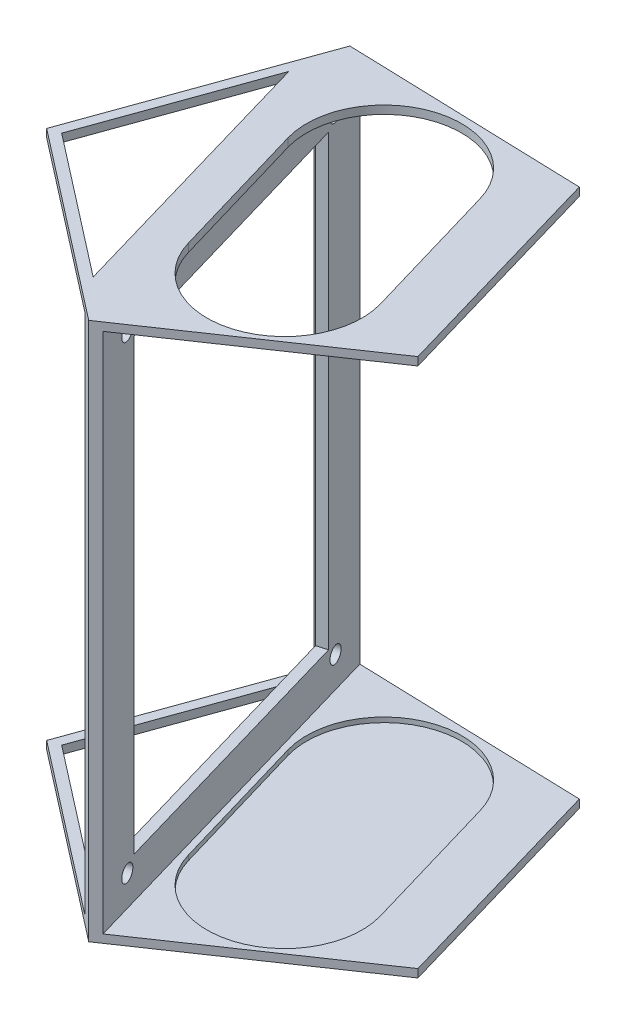
SolidWorks part; units mm, degrees
ref_plane "Front Plane" through (0, 0, 0) normal (0, 0, 1) x (1, 0, 0)
ref_plane "Top Plane" through (0, 0, 0) normal (0, 1, 0) x (1, 0, 0)
ref_plane "Right Plane" through (0, 0, 0) normal (1, 0, 0) x (0, 0, -1)
sketch "Sketch1" plane through (0, 0, 0) normal (0, 1, 0) x (1, 0, 0)
  line L1 (23.2611, -8.3705) -> (15.1489, 19.536)
  line L2 (15.1489, 19.536) -> (-13.8986, 20.4445)
  line L3 (-13.8986, 20.4445) -> (-23.7387, -6.9006)
  line L4 (-23.7387, -6.9006) -> (-0.7728, -24.7093)
  line L5 (-0.7728, -24.7093) -> (23.2611, -8.3705)
  circle A0 centre (0, 0) radius 20 construction
  point P1 (0, 0)
extrude "Boss-Extrude1" add sketch "Sketch1" along normal blind 1
sketch "Sketch2" plane through (0, 1, 0) normal (0, 1, 0) x (1, 0, 0)
  line L0 (-0.7728, -24.7093) -> (-13.8986, 20.4445) construction
  line L1 (-2.9239, -23.0412) -> (-14.8202, 17.8832)
  line L2 (-23.7387, -6.9006) -> (-0.7728, -24.7093) construction
  line L3 (-13.8986, 20.4445) -> (-23.7387, -6.9006) construction
  line L4 (0.2707, -23.9999) -> (-12.6374, 20.405)
  line L5 (-0.7728, -24.7093) -> (23.2611, -8.3705) construction
  line L6 (15.1489, 19.536) -> (-13.8986, 20.4445) construction
  line L7 (-14.8202, 17.8832) -> (-13.8986, 20.4445)
  line L13 (-0.7728, -24.7093) -> (23.2611, -8.3705)
  line L14 (23.2611, -8.3705) -> (15.1489, 19.536)
  line L15 (15.1489, 19.536) -> (-13.8986, 20.4445)
  line L16 (-13.8986, 20.4445) -> (-23.7387, -6.9006)
  line L17 (-23.7387, -6.9006) -> (-0.7728, -24.7093)
  line L18 (-0.7728, -24.7093) -> (0.2707, -23.9999)
  line L20 (-12.6374, 20.405) -> (-13.8986, 20.4445)
  line L21 (-13.8986, 20.4445) -> (-14.8202, 17.8832)
  line L22 (-2.9239, -23.0412) -> (-0.7728, -24.7093)
  line M10 (-0.7728, -24.7093) -> (23.2611, -8.3705)
  line M12 (15.1489, 19.536) -> (-13.8986, 20.4445)
  line M13 (-13.8986, 20.4445) -> (-23.7387, -6.9006)
  line M14 (-23.7387, -6.9006) -> (-0.7728, -24.7093)
  dimension "D1" = 1.2
  dimension "D2" = 1.6
  dimension "D3" = 0
extrude "Boss-Extrude2" add sketch "Sketch2" along normal blind 65 contours L0 L1 M14 M13 | L0 L4 M10 M12
sketch "Sketch3" plane through (0, 1, 0) normal (0, 1, 0) x (1, 0, 0)
  line L0 (10.2933, 12.2338) -> (15.3581, -5.0389)
  line L3 (-7.9391, 6.8877) -> (-2.8743, -10.3851)
  line L4 (-23.7201, -6.9646) -> (0.0025, -0.0086) construction
  line L5 (6.2419, -7.712) -> (1.1771, 9.5607) construction
  arc A0 (15.3581, -5.0389) -> (-2.8743, -10.3851) centre (6.2419, -7.712) cw
  arc A1 (10.2933, 12.2338) -> (-7.9391, 6.8877) centre (1.1771, 9.5607) ccw
  point P6 (-1.496, 18.6769)
  point P7 (8.915, -16.8282)
  dimension "D1" = 37
  dimension "D2" = 19
sketch "Sketch4" plane through (-8.8721, 0, 2.579) normal (-0.9603, 0, 0.2791) x (0.2791, 0, 0.9603)
  line L0 (-21.3092, 66) -> (21.3092, 1) construction
  line L1 (21.3092, 1) -> (-21.3092, 1) construction
  line L2 (21.3092, 66) -> (-21.3092, 1) construction
  line L3 (0, 63.5) -> (0, 3.5) construction
  line L4 (-20, 63.5) -> (20, 63.5)
  line L5 (-20, 63.5) -> (-20, 3.5)
  line L6 (-20, 3.5) -> (20, 3.5)
  line L7 (20, 63.5) -> (20, 3.5)
  line L8 (-20, 63.5) -> (20, 3.5) construction
  line L9 (-20, 3.5) -> (20, 63.5) construction
  line L10 (-20, 33.5) -> (20, 33.5) construction
  point P12 (0, 33.5)
  dimension "D1" = 40
  dimension "D2" = 60
extrude "Cut-Extrude1" cut sketch "Sketch4" against normal blind 1.5
sketch "Sketch5" plane through (-7.4317, 0, 2.1603) normal (-0.9603, 0, 0.2791) x (0.2791, 0, 0.9603)
  line L8 (17.5, 6) -> (17.5, 61)
  line L9 (17.5, 61) -> (-17.5, 61)
  line L10 (-17.5, 61) -> (-17.5, 6)
  line L11 (-17.5, 6) -> (17.5, 6)
  line L12 (17.5, 6) -> (17.5, 61)
  line L13 (17.5, 61) -> (-17.5, 61)
  line L14 (-17.5, 61) -> (-17.5, 6)
  line L15 (-17.5, 6) -> (17.5, 6)
  dimension "D1" = 2.5
extrude "Cut-Extrude2" cut sketch "Sketch5" against normal up to surface (1.3 mm away) up to face at (-6.1834, 33.5, 1.7974)
sketch "Sketch7" plane through (0, 66, 0) normal (0, 1, 0) x (1, 0, 0)
  line L5 (-0.7728, -24.7093) -> (23.2611, -8.3705)
  line L6 (-23.7387, -6.9006) -> (-0.7728, -24.7093)
  line L7 (-13.8986, 20.4445) -> (-23.7387, -6.9006)
  line L8 (15.1489, 19.536) -> (-13.8986, 20.4445)
  line L9 (23.2611, -8.3705) -> (15.1489, 19.536)
  line L10 (-0.7728, -24.7093) -> (23.2611, -8.3705)
  line L11 (-23.7387, -6.9006) -> (-0.7728, -24.7093)
  line L12 (-13.8986, 20.4445) -> (-23.7387, -6.9006)
  line L13 (15.1489, 19.536) -> (-13.8986, 20.4445)
  line L14 (23.2611, -8.3705) -> (15.1489, 19.536)
  dimension "D1" = 0
extrude "Boss-Extrude3" add sketch "Sketch7" against normal blind 1
sketch "Sketch6" plane through (0, 1, 0) normal (0, 1, 0) x (1, 0, 0)
  line L6 (-22.3144, -6.4866) -> (-5.1071, -19.8298)
  line L7 (-5.1071, -19.8298) -> (-14.9416, 14.0018)
  line L8 (-14.9416, 14.0018) -> (-22.3144, -6.4866)
  line L9 (-22.3144, -6.4866) -> (-5.1071, -19.8298)
  line L10 (-5.1071, -19.8298) -> (-14.9416, 14.0018)
  line L11 (-14.9416, 14.0018) -> (-22.3144, -6.4866)
  dimension "D1" = 1.2
extrude "Cut-Extrude3" cut sketch "Sketch6" along normal up to surface and the other way up to surface up to face at (0, 66, 0) other way up to face at (0, 0, 0)
extrude "Cut-Extrude4" cut sketch "Sketch3" against normal blind 0.6 and the other way up to surface other way up to face at (0, 66, 0)
sketch "Sketch8" plane through (-7.4317, 0, 2.1603) normal (-0.9603, 0, 0.2791) x (0.2791, 0, 0.9603)
  line L0 (0, 3.5) -> (0, 63.5) construction
  line L1 (-20, 3.5) -> (20, 3.5) construction
  line L2 (20, 63.5) -> (-20, 63.5) construction
  line L3 (-20, 33.5) -> (20, 33.5) construction
  line L4 (-20, 63.5) -> (-20, 3.5) construction
  line L5 (20, 3.5) -> (20, 63.5) construction
  circle A0 centre (-18.75, 4.75) radius 1
  circle A1 centre (18.75, 4.75) radius 1
  circle A2 centre (-18.75, 62.25) radius 1
  circle A3 centre (18.75, 62.25) radius 1
  dimension "D1" = 2
  dimension "D2" = 1.25
  dimension "D3" = 1.25
extrude "Cut-Extrude5" cut sketch "Sketch8" against normal up to surface (1.3 mm away) up to face at (-6.1834, 33.5, 1.7974)
